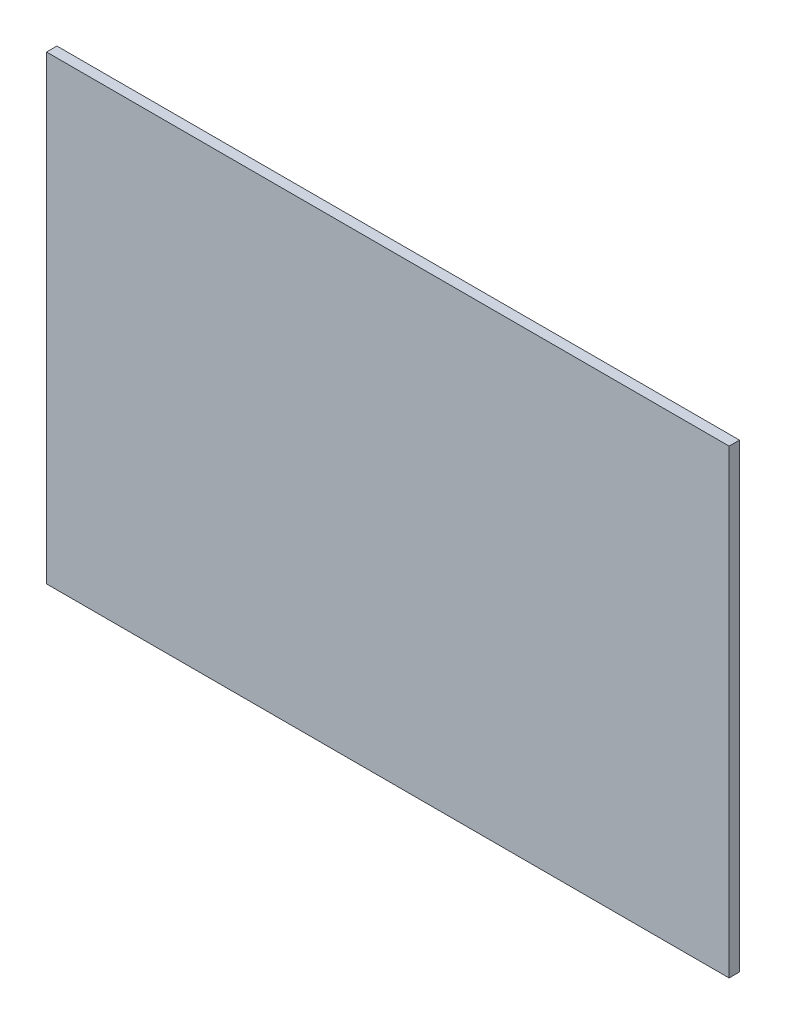
SolidWorks part; units mm, degrees
ref_plane "Front Plane" through (0, 0, 0) normal (0, 0, 1) x (1, 0, 0)
ref_plane "Top Plane" through (0, 0, 0) normal (0, 1, 0) x (1, 0, 0)
ref_plane "Right Plane" through (0, 0, 0) normal (1, 0, 0) x (0, 0, -1)
sketch "Sketch1" plane through (0, 0, 0) normal (0, 0, 1) x (1, 0, 0)
  line L1 (-52.2224, -35.2425) -> (52.2224, -35.2425)
  line L2 (-52.2224, -35.2425) -> (-52.2224, 35.2425)
  line L3 (-52.2224, 35.2425) -> (52.2224, 35.2425)
  line L4 (52.2224, -35.2425) -> (52.2224, 35.2425)
  line L5 (-52.2224, -35.2425) -> (52.2224, 35.2425) construction
  line L6 (-52.2224, 35.2425) -> (52.2224, -35.2425) construction
  point P0 (0, 0)
  dimension "D1" = 70.485
  dimension "D2" = 104.4448
extrude "Boss-Extrude1" add sketch "Sketch1" along normal blind 1.5875
